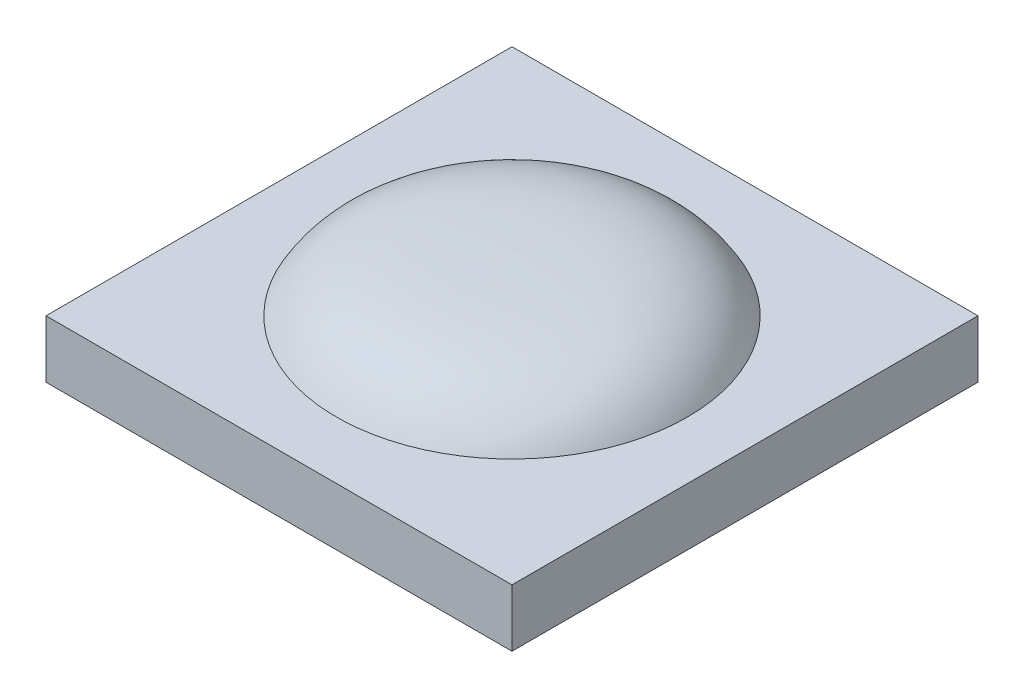
SolidWorks part; units mm, degrees
ref_plane "Front" through (0, 0, 0) normal (0, 0, 1) x (1, 0, 0)
ref_plane "Top" through (0, 0, 0) normal (0, 1, 0) x (1, 0, 0)
ref_plane "Right" through (0, 0, 0) normal (1, 0, 0) x (0, 0, -1)
sketch "Sketch1" plane through (0, 0, 0) normal (0, 0, 1) x (1, 0, 0)
  line L0 (0, 25) -> (0, 10) construction
  line L1 (31.5, 19.8898) -> (31.5, -17.8473) construction
  line L2 (0, 0) -> (31.5, 0) construction
  line L3 (0, 25) -> (0, 0) construction
  line L4 (31.5, 0) -> (30.5, 0) construction
  line L5 (0, 10) -> (0, 0)
  line L6 (0, 0) -> (30.5, 0)
  spline S0 degree 3 poles (0, 25) (1.3715, 25) (4.0902, 24.3027) (10.7515, 17.1368) (25.5788, 15.0702) (31.0385, 6.4502) (31.5, 0) knots 0 0 0 0 0.091246 0.195023 0.675457 1 1 1 1 construction
  spline S1 degree 3 poles (30.5, 0) (24.4624, 10.5881) (11.1572, 9.4928) (0, 10) knots 0 0 0 0 1 1 1 1
  dimension "D1" = 25
  dimension "D4" = 31.5
  dimension "D2" = 1
  dimension "D3" = 15
revolve "Revolve1" add sketch "Sketch1" angle 360 about L5
sketch "Sketch2" plane through (0, 0, 0) normal (0, 1, 0) x (1, 0, 0)
  line L1 (-40.5, -40.5) -> (40.5, -40.5)
  line L2 (-40.5, -40.5) -> (-40.5, 40.5)
  line L3 (-40.5, 40.5) -> (40.5, 40.5)
  line L4 (40.5, -40.5) -> (40.5, 40.5)
  line L5 (-40.5, -40.5) -> (40.5, 40.5) construction
  line L6 (-40.5, 40.5) -> (40.5, -40.5) construction
  point P0 (0, 0)
  dimension "D1" = 81
extrude "Boss-Extrude1" add sketch "Sketch2" against normal blind 10
equation "\"CutAngle\"= 2"
